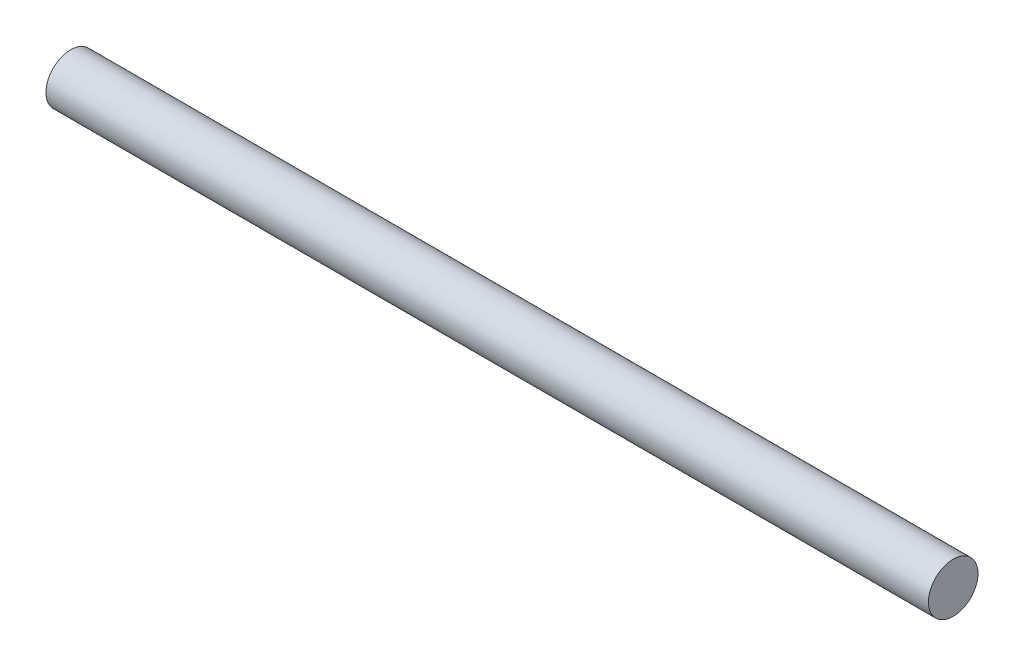
SolidWorks part; units mm, degrees
ref_plane "Front Plane" through (0, 0, 0) normal (0, 0, 1) x (1, 0, 0)
ref_plane "Top Plane" through (0, 0, 0) normal (0, 1, 0) x (1, 0, 0)
ref_plane "Right Plane" through (0, 0, 0) normal (1, 0, 0) x (0, 0, -1)
sketch "Sketch1" plane through (0, 0, 0) normal (0, 0, 1) x (1, 0, 0)
  line L0 (196.3562, 0) -> (-196.3562, 0) construction
  line L3 (127, 7.5) -> (-140, 7.5)
  line L4 (0, -42.6677) -> (0, 42.6677) construction
  line L7 (127, 7.5) -> (127, 0)
  line L8 (127, 0) -> (-127, 0)
  line L9 (-140, 7.5) -> (-140, 5.5)
  line L10 (-140, 5.5) -> (-127, 5.5)
  line L11 (-127, 5.5) -> (-127, 0)
  point P3 (-89.3146, 0)
  point P5 (50.1252, 9.9074)
  point P6 (-196.3562, 0)
  point P7 (-127, 4.384)
  point P10 (0, 0)
  point P12 (127, 0)
  dimension "D1" = 127
  dimension "D2" = 140
  dimension "D3" = 13
  dimension "D4" = 15
  dimension "D5" = 11
revolve "Revolve1" add sketch "Sketch1" angle 360 about L0
